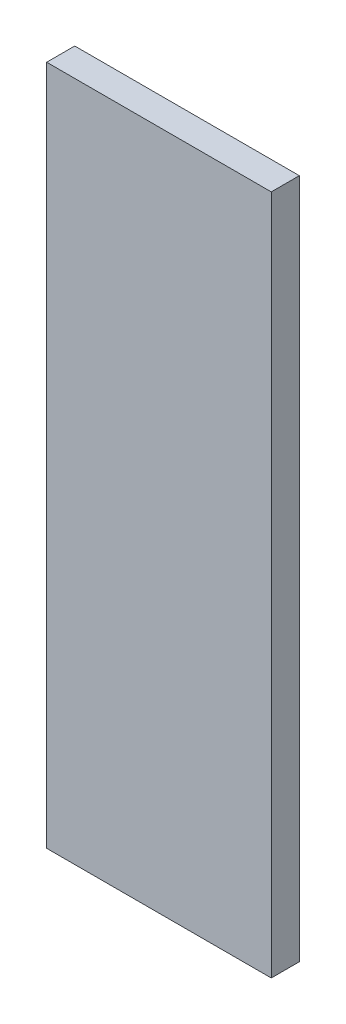
SolidWorks part; units mm, degrees
ref_plane "Front Plane" through (0, 0, 0) normal (0, 0, 1) x (1, 0, 0)
ref_plane "Top Plane" through (0, 0, 0) normal (0, 1, 0) x (1, 0, 0)
ref_plane "Right Plane" through (0, 0, 0) normal (1, 0, 0) x (0, 0, -1)
sketch "Sketch2" plane through (0, 0, 0) normal (0, 0, 1) x (1, 0, 0)
  line L1 (-25.4, -76.9937) -> (25.4, -76.9937)
  line L2 (-25.4, -76.9937) -> (-25.4, 76.9938)
  line L3 (-25.4, 76.9938) -> (25.4, 76.9938)
  line L4 (25.4, -76.9937) -> (25.4, 76.9938)
  line L5 (-25.4, -76.9937) -> (25.4, 76.9938) construction
  line L6 (-25.4, 76.9938) -> (25.4, -76.9937) construction
  point P0 (0, 0)
  dimension "D1" = 50.8
  dimension "D2" = 153.9875
extrude "Boss-Extrude1" add sketch "Sketch2" along normal blind 6.35
